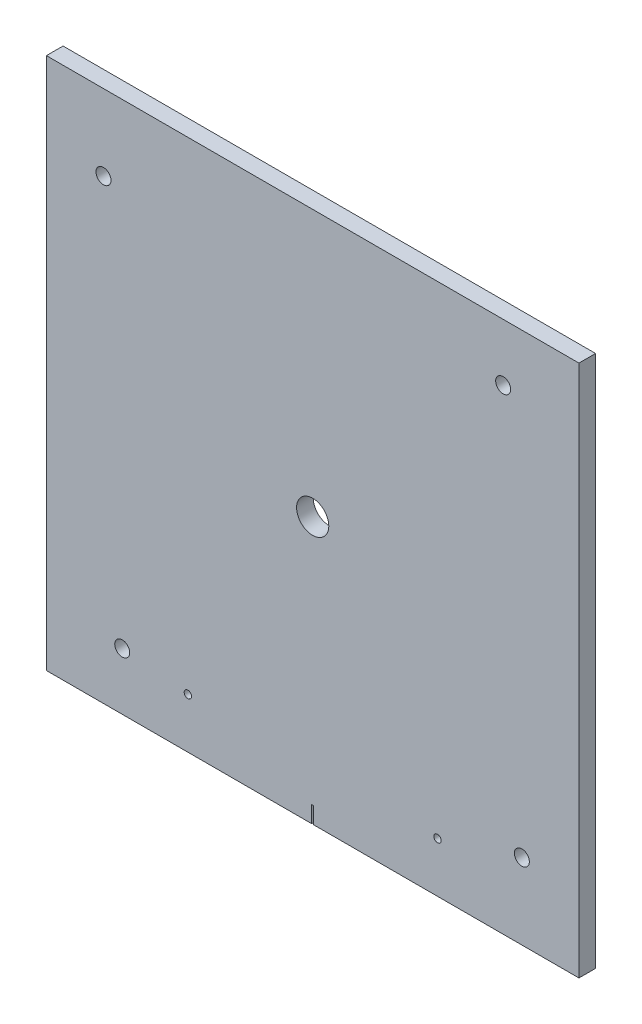
SolidWorks part; units mm, degrees
ref_plane "Front Plane" through (0, 0, 0) normal (0, 0, 1) x (1, 0, 0)
ref_plane "Top Plane" through (0, 0, 0) normal (0, 1, 0) x (1, 0, 0)
ref_plane "Right Plane" through (0, 0, 0) normal (1, 0, 0) x (0, 0, -1)
sketch "Sketch1" plane through (0, 0, 0) normal (0, 0, 1) x (1, 0, 0)
  line L0 (-101.6, 101.6) -> (101.6, -101.6) construction
  line L1 (-101.6, 101.6) -> (101.6, 101.6)
  line L2 (-101.6, 101.6) -> (-101.6, -101.6)
  line L3 (-101.6, -101.6) -> (101.6, -101.6)
  line L4 (101.6, 101.6) -> (101.6, -101.6)
  line L5 (101.6, -101.6) -> (100.9091, -101.3697) construction
  dimension "D1" = 203.2
  dimension "D2" = 203.2
extrude "Extrude1" add sketch "Sketch1" along normal blind 6.35
sketch "Sketch2" plane through (0, 0, 6.35) normal (0, 0, 1) x (1, 0, 0)
  circle A0 centre (0, 0) radius 6.1468
  dimension "D1" = 12.2936
extrude "Extrude2" cut sketch "Sketch2" against normal through all
sketch "Sketch3" plane through (0, 0, 6.35) normal (0, 0, 1) x (1, 0, 0)
  line L0 (-1000, 0) -> (49000, 0) construction
  line L1 (0, -1000) -> (0, 49000) construction
  line L2 (0, 0) -> (25000, -43301.2702) construction
  line L3 (0, 0) -> (-25000, -43301.2702) construction
  circle A0 centre (-47.625, -82.4889) radius 1.4097
  circle A1 centre (47.625, -82.4889) radius 1.4097
  dimension "D2" = 2.8194
  dimension "D4" = 2.8194
  dimension "D1" = 60
  dimension "D3" = 95.25
  dimension "D5" = 95.25
extrude "Extrude3" cut sketch "Sketch3" against normal through all
sketch "Sketch4" plane through (0, 0, 6.35) normal (0, 0, 1) x (1, 0, 0)
  line L0 (0, -1000) -> (0, 49000) construction
  line L1 (-0.3969, -961.5871) -> (-0.3969, 49038.4129) construction
  line L2 (0.3969, -960.1422) -> (0.3969, 49039.8578) construction
  line L3 (-0.3969, -95.25) -> (0.3969, -95.25)
  line L4 (-0.3969, -95.25) -> (-0.3969, -101.6)
  line L5 (-0.3969, -101.6) -> (0.3969, -101.6)
  line L6 (0.3969, -101.6) -> (0.3969, -95.25)
  dimension "D1" = 0.3969
  dimension "D2" = 0.3969
  dimension "D3" = 95.25
  dimension "D4" = 101.6
extrude "Extrude4" cut sketch "Sketch4" against normal blind 6.35
sketch "Sketch5" plane through (0, 0, 6.35) normal (0, 0, 1) x (1, 0, 0)
  line L0 (-1000, 0) -> (49000, 0) construction
  line L1 (0, -1000) -> (0, 49000) construction
  line L2 (0, 0) -> (-94.4514, 85.9922) construction
  line L3 (0, 0) -> (82.2317, 90.3209) construction
  line L4 (0, 0) -> (-86.8631, -95.4079) construction
  line L5 (0, 0) -> (95.4079, -86.8631) construction
  circle A0 centre (-79.8229, 72.6739) radius 2.8575
  circle A1 centre (72.6739, 79.8229) radius 2.8575
  circle A2 centre (-72.6739, -79.8229) radius 2.8575
  circle A3 centre (79.8229, -72.6739) radius 2.8575
  dimension "D6" = 5.715
  dimension "D7" = 5.715
  dimension "D9" = 5.715
  dimension "D10" = 5.715
  dimension "D1" = 90
  dimension "D2" = 90
  dimension "D3" = 90
  dimension "D4" = 90
  dimension "D5" = 107.95
  dimension "D8" = 107.95
  dimension "D11" = 107.95
  dimension "D12" = 107.95
extrude "Extrude5" cut sketch "Sketch5" against normal through all
